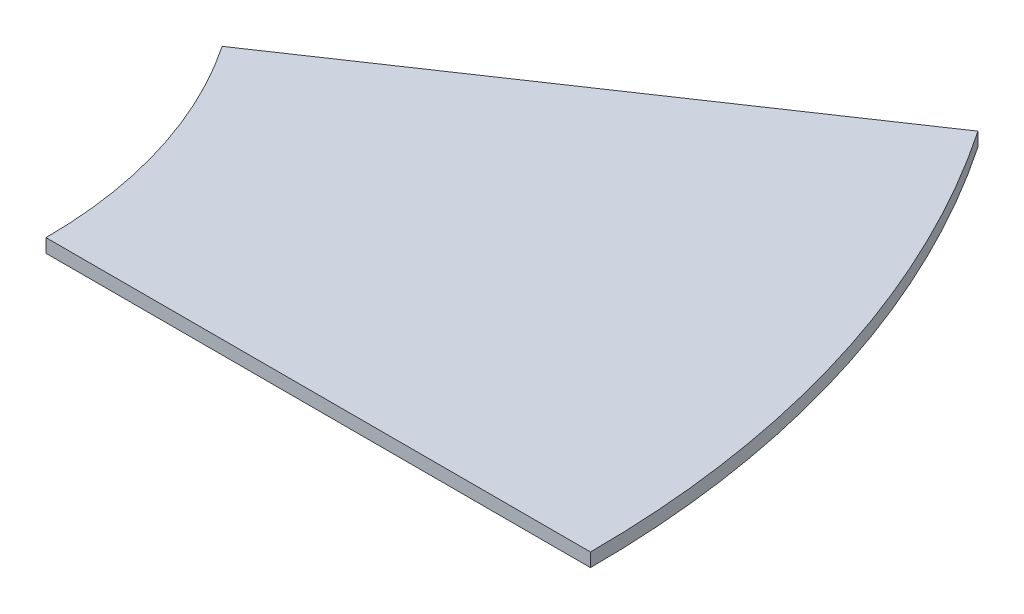
SolidWorks part; units mm, degrees
ref_plane "Front" through (0, 0, 0) normal (0, 0, 1) x (1, 0, 0)
ref_plane "Top" through (0, 0, 0) normal (0, 1, 0) x (1, 0, 0)
ref_plane "Right" through (0, 0, 0) normal (1, 0, 0) x (0, 0, -1)
sketch "草图1" plane through (0, 0, 0) normal (0, 1, 0) x (1, 0, 0)
  line L0 (0, 0) -> (110, 0) construction
  line L1 (91.1941, 61.5112) -> (0, 0) construction
  line L2 (91.1941, 61.5112) -> (41.4519, 27.9596)
  line L3 (110, 0) -> (50, 0)
  arc A0 (110, 0) -> (91.1941, 61.5112) centre (0, 0) ccw
  arc A1 (50, 0) -> (41.4519, 27.9596) centre (0, 0) ccw
  dimension "D2" = 50
  dimension "D3" = 110
  dimension "D1" = 34
extrude "凸台-拉伸1" add sketch "草图1" along normal blind 1.5 contours L3 A1 L2 A0
